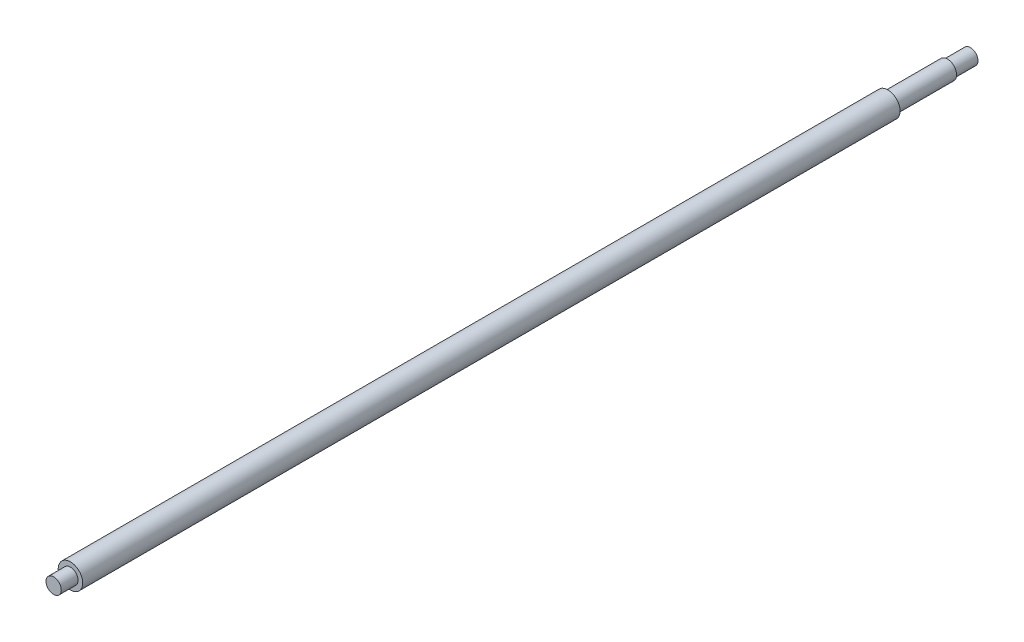
SolidWorks part; units mm, degrees
ref_plane "Plan de face" through (0, 0, 0) normal (0, 0, 1) x (1, 0, 0)
ref_plane "Plan de dessus" through (0, 0, 0) normal (0, 1, 0) x (1, 0, 0)
ref_plane "Plan de droite" through (0, 0, 0) normal (1, 0, 0) x (0, 0, -1)
sketch "Esquisse1" plane through (0, 0, 0) normal (0, 0, 1) x (1, 0, 0)
  circle A0 centre (0, 0) radius 5
  dimension "D1" = 10
extrude "Boss.-Extru.1" add sketch "Esquisse1" along normal blind 15
sketch "Esquisse2" plane through (0, 0, 15) normal (0, 0, 1) x (1, 0, 0)
  circle A0 centre (0, 0) radius 6
  dimension "D1" = 12
extrude "Boss.-Extru.2" add sketch "Esquisse2" along normal blind 39
sketch "Esquisse3" plane through (0, 0, 54) normal (0, 0, 1) x (1, 0, 0)
  circle A0 centre (0, 0) radius 8
  dimension "D1" = 16
extrude "Boss.-Extru.3" add sketch "Esquisse3" along normal blind 535
sketch "Esquisse4" plane through (0, 0, 589) normal (0, 0, 1) x (1, 0, 0)
  circle A0 centre (0, 0) radius 5
  dimension "D1" = 10
extrude "Boss.-Extru.4" add sketch "Esquisse4" along normal blind 11
